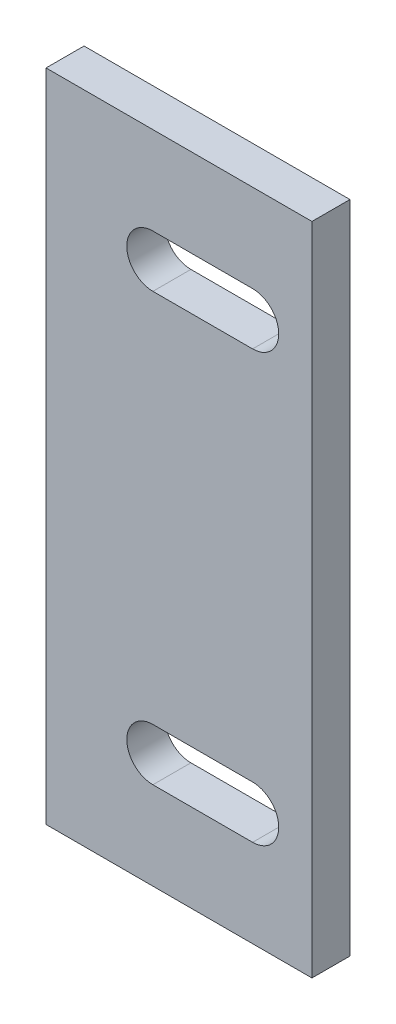
SolidWorks part; units mm, degrees
material "Polyetheretherketone (PEEK)"
ref_plane "Front Plane" through (0, 0, 0) normal (0, 0, 1) x (1, 0, 0)
ref_plane "Top Plane" through (0, 0, 0) normal (0, 1, 0) x (1, 0, 0)
ref_plane "Right Plane" through (0, 0, 0) normal (1, 0, 0) x (0, 0, -1)
ref_plane "Plane1" through (0, 0, 4) normal (0, 0, 1) x (1, 0, 0)
sketch "Sketch1" plane through (0, 0, 4) normal (0, 0, 1) x (1, 0, 0)
  line L0 (11.25, 25.25) -> (21.75, 25.25)
  line L1 (21.75, 19.75) -> (11.25, 19.75)
  line L2 (11.25, -19.75) -> (21.75, -19.75)
  line L3 (21.75, -25.25) -> (11.25, -25.25)
  line L4 (0, -34.5) -> (28, -34.5)
  line L5 (28, -34.5) -> (28, 34.5)
  line L6 (28, 34.5) -> (0, 34.5)
  line L7 (0, 34.5) -> (0, -34.5)
  arc A0 (21.75, 25.25) -> (21.75, 19.75) centre (21.75, 22.5) cw
  arc A1 (11.25, 19.75) -> (11.25, 25.25) centre (11.25, 22.5) cw
  arc A2 (21.75, -19.75) -> (21.75, -25.25) centre (21.75, -22.5) cw
  arc A3 (11.25, -25.25) -> (11.25, -19.75) centre (11.25, -22.5) cw
  dimension "D1" = 2.75
  dimension "D2" = 2.75
  dimension "D3" = 11.25
  dimension "D4" = 21.75
  dimension "D5" = 28
  dimension "D6" = 12
  dimension "D7" = 57
  dimension "D8" = 69
  dimension "D9" = 34.5
extrude "Boss-Extrude1" add sketch "Sketch1" against normal blind 4
